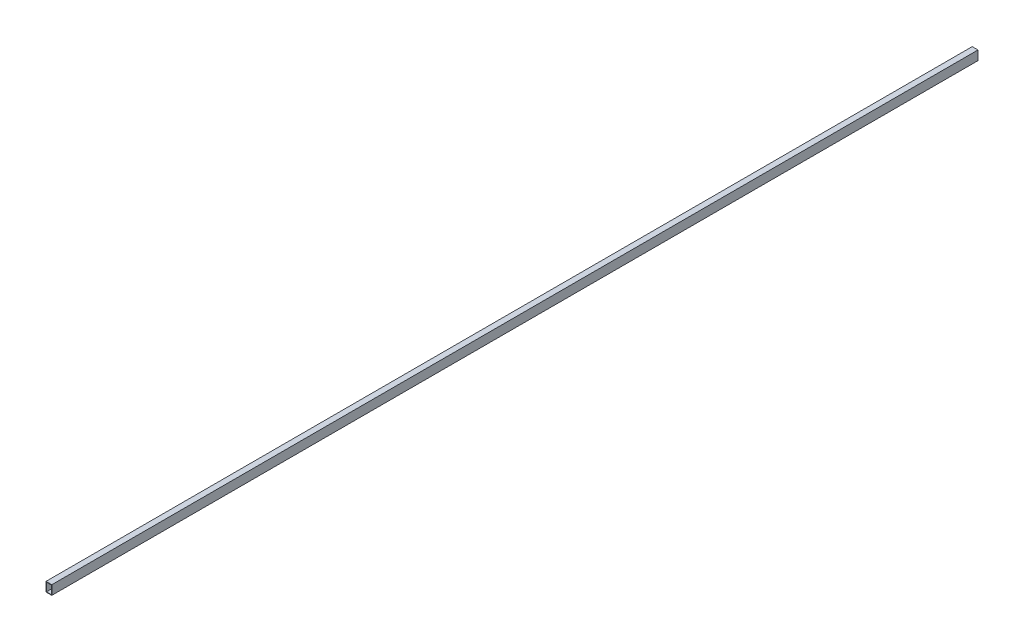
SolidWorks part; units mm, degrees
material "1060 Alloy"
ref_plane "Front Plane" through (0, 0, 0) normal (0, 0, 1) x (1, 0, 0)
ref_plane "Top Plane" through (0, 0, 0) normal (0, 1, 0) x (1, 0, 0)
ref_plane "Right Plane" through (0, 0, 0) normal (1, 0, 0) x (0, 0, -1)
sketch "Sketch1" plane through (0, 0, 0) normal (0, 0, 1) x (1, 0, 0)
  line L1 (-25, 40) -> (25, 40)
  line L2 (-25, 40) -> (-25, -40)
  line L3 (-25, -40) -> (25, -40)
  line L4 (25, 40) -> (25, -40)
  point P0 (0, 0)
  point P7 (0, 0)
  dimension "D1" = 80
  dimension "D2" = 50
extrude "Boss-Extrude1" add sketch "Sketch1" along normal blind 8000 contours L1 L4 L3 L2
sketch "Sketch2" plane through (0, 0, 0) normal (0, 0, -1) x (-1, 0, 0)
  line L1 (-21, 36) -> (21, 36)
  line L2 (-21, 36) -> (-21, -36)
  line L3 (-21, -36) -> (21, -36)
  line L4 (21, 36) -> (21, -36)
  line L5 (-21, 36) -> (21, -36) construction
  line L6 (-21, -36) -> (21, 36) construction
  point P0 (0, 0)
  dimension "D1" = 42
  dimension "D2" = 72
extrude "Cut-Extrude1" cut sketch "Sketch2" against normal blind 8000
